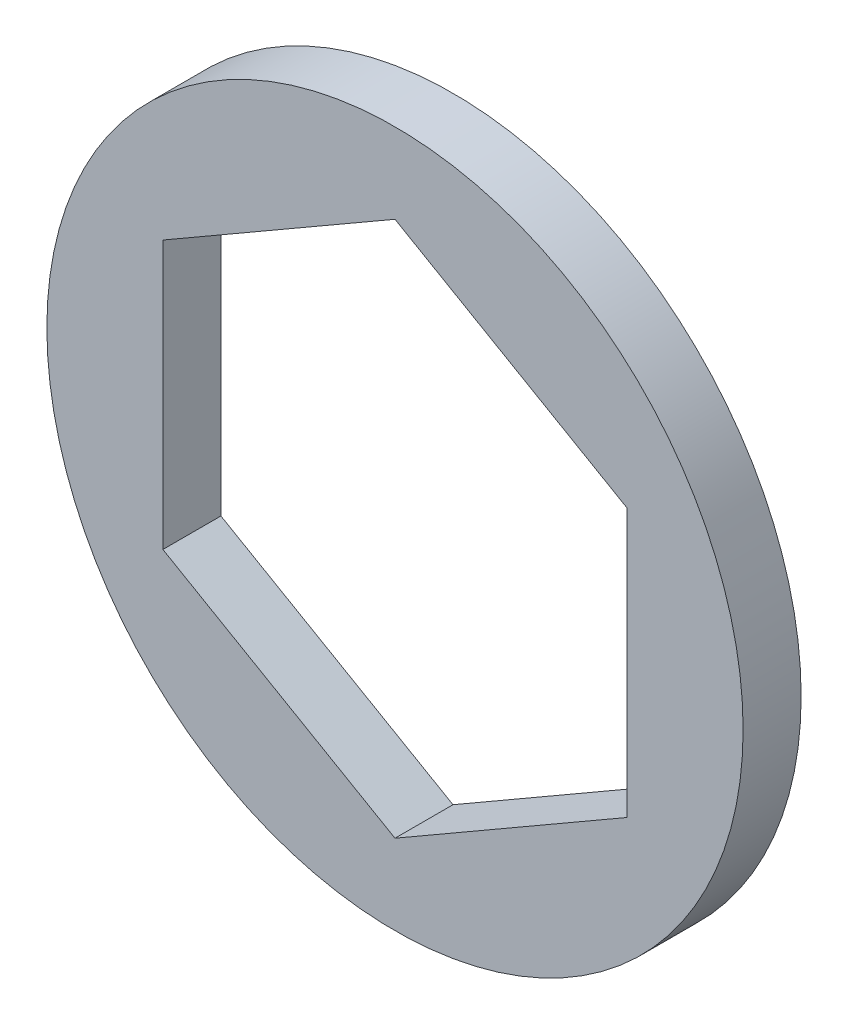
SolidWorks part; units mm, degrees
material "PET"
ref_plane "Front Plane" through (0, 0, 0) normal (0, 0, 1) x (1, 0, 0)
ref_plane "Top Plane" through (0, 0, 0) normal (0, 1, 0) x (1, 0, 0)
ref_plane "Right Plane" through (0, 0, 0) normal (1, 0, 0) x (0, 0, -1)
sketch "Sketch1" plane through (0, 0, 0) normal (0, 0, 1) x (1, 0, 0)
  line L1 (0, 7.3323) -> (-6.35, 3.6662)
  line L2 (-6.35, 3.6662) -> (-6.35, -3.6662)
  line L3 (-6.35, -3.6662) -> (0, -7.3323)
  line L4 (0, -7.3323) -> (6.35, -3.6662)
  line L5 (6.35, -3.6662) -> (6.35, 3.6662)
  line L6 (6.35, 3.6662) -> (0, 7.3323)
  circle A0 centre (0, 0) radius 9.525
  circle A1 centre (0, 0) radius 6.35 construction
  dimension "D1" = 12.7
  dimension "D3" = 19.05
extrude "Boss-Extrude2" add sketch "Sketch1" along normal blind 1.5875
